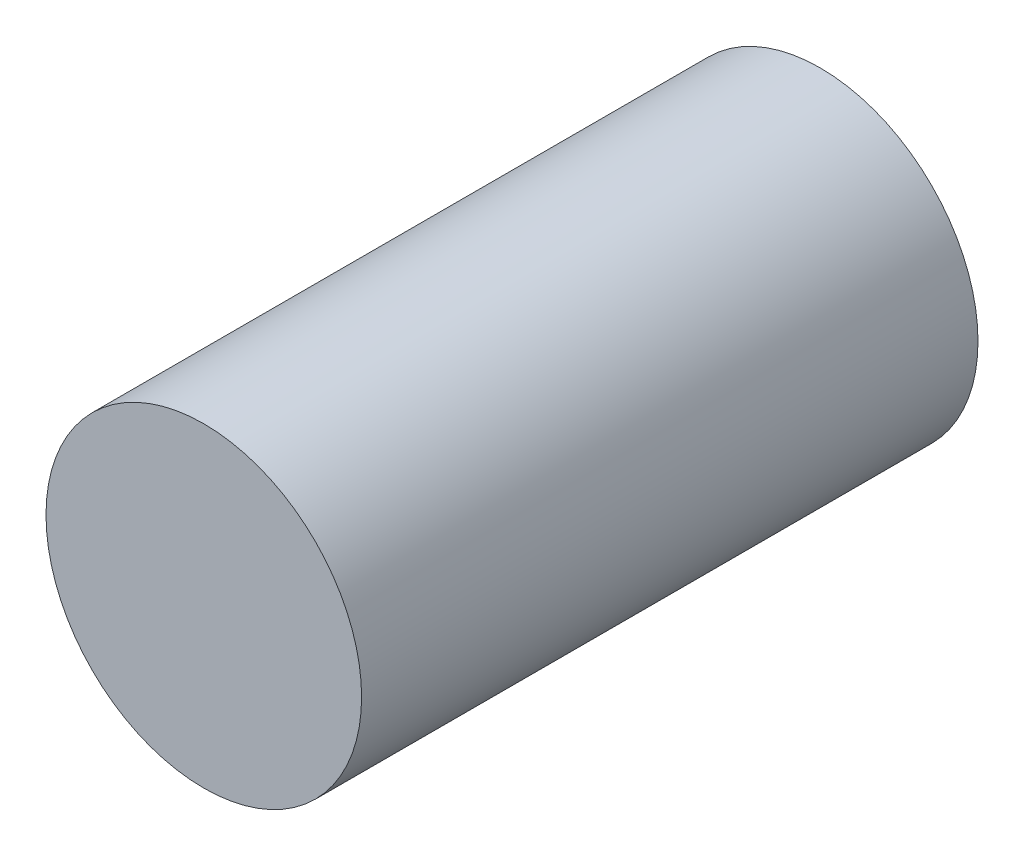
SolidWorks part; units mm, degrees
ref_plane "Front Plane" through (0, 0, 0) normal (0, 0, 1) x (1, 0, 0)
ref_plane "Top Plane" through (0, 0, 0) normal (0, 1, 0) x (1, 0, 0)
ref_plane "Right Plane" through (0, 0, 0) normal (1, 0, 0) x (0, 0, -1)
sketch "Sketch1" plane through (0, 0, 0) normal (0, 0, 1) x (1, 0, 0)
  circle A0 centre (0, 0) radius 3.2
  dimension "D1" = 6.4
extrude "Boss-Extrude1" add sketch "Sketch1" along normal blind 12.5
scale "缩放比例1" scale about centroid uniform scaling yes scale factor 2
